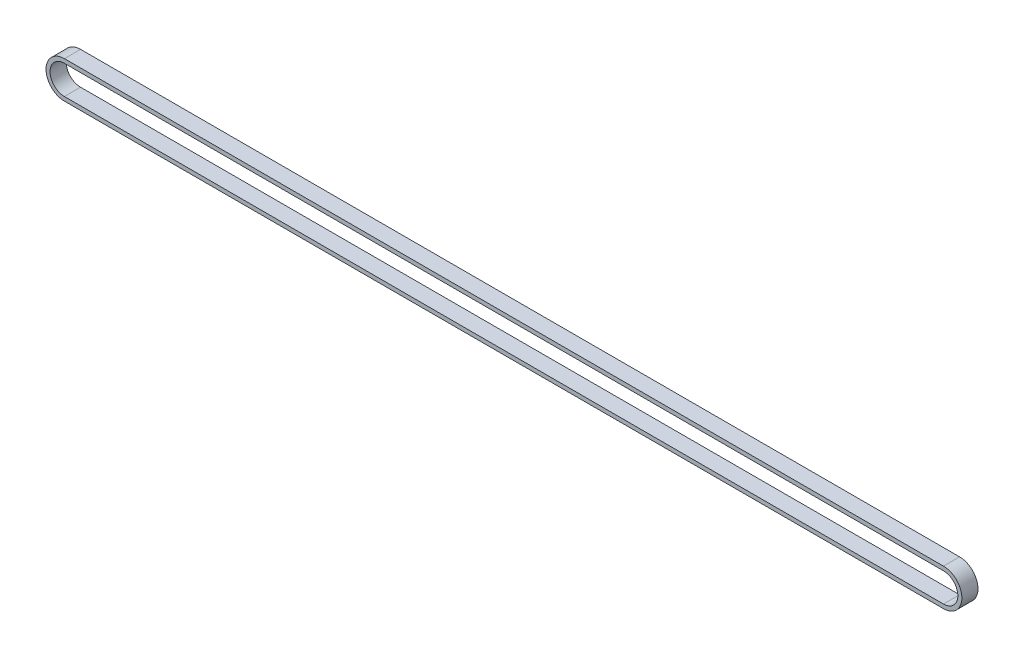
SolidWorks part; units mm, degrees
material "EPDM 60 Durometer"
ref_plane "Front" through (0, 0, 0) normal (0, 0, 1) x (1, 0, 0)
ref_plane "Top" through (0, 0, 0) normal (0, 1, 0) x (1, 0, 0)
ref_plane "Right" through (0, 0, 0) normal (1, 0, 0) x (0, 0, -1)
sketch "Sketch1" plane through (0, 0, 0) normal (0, 0, 1) x (1, 0, 0)
  line L0 (-163.5, 0) -> (163.5, 0) construction
  line L1 (-163.5, 6.85) -> (163.5, 6.85)
  line L2 (-163.5, -6.85) -> (163.5, -6.85)
  arc A0 (-163.5, 6.85) -> (-163.5, -6.85) centre (-163.5, 0) ccw
  arc A1 (163.5, -6.85) -> (163.5, 6.85) centre (163.5, 0) ccw
  point P2 (0, 0)
  dimension "D1" = 6.85
  dimension "D3" = 675.5199
  dimension "D2" = 327
extrude "Extrude-Thin1" add sketch "Sketch1" along normal mid plane 6 thin contours L1 A1 L2 A0
